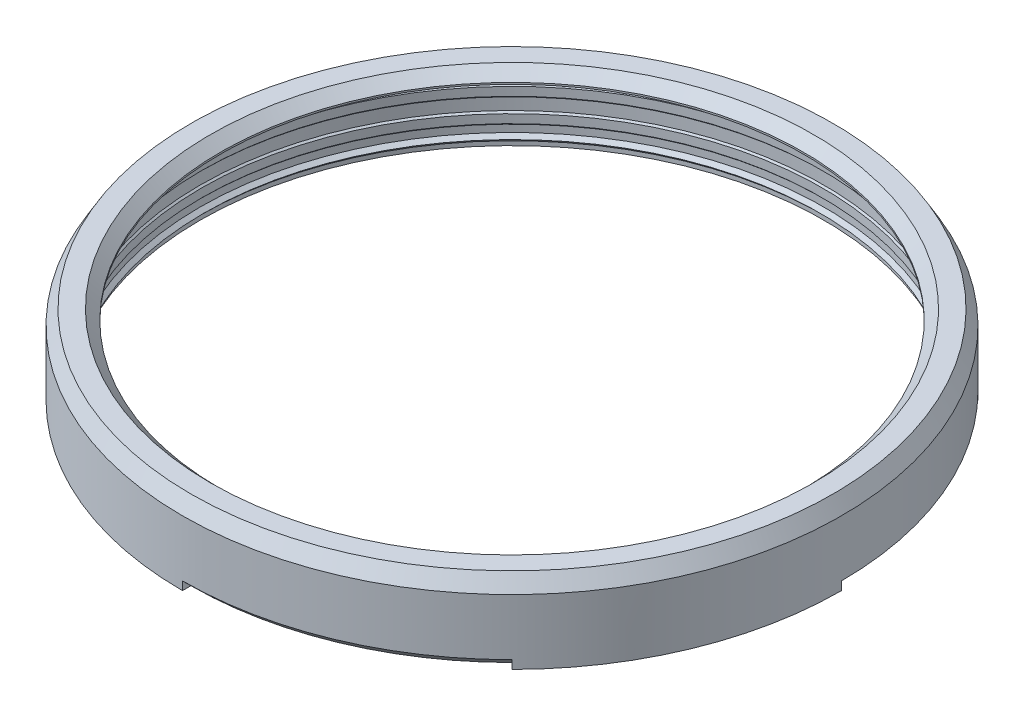
SolidWorks part; units mm, degrees
ref_plane "前视基准面" through (0, 0, 0) normal (0, 0, 1) x (1, 0, 0)
ref_plane "上视基准面" through (0, 0, 0) normal (0, 1, 0) x (1, 0, 0)
ref_plane "右视基准面" through (0, 0, 0) normal (1, 0, 0) x (0, 0, -1)
sketch "草图1" plane through (0, 0, 0) normal (0, 1, 0) x (1, 0, 0)
  circle A0 centre (0, 0) radius 39
  dimension "D1" = 78
extrude "凸台-拉伸1" add sketch "草图1" along normal blind 2
sketch "草图2" plane through (0, 0, 0) normal (-0.866, 0, 0.5) x (0.5, 0, 0.866)
  line L0 (36.93, -8) -> (36.93, -7.5)
  line L1 (36.93, -7.5) -> (36.505, -7.075)
  line L2 (36.505, -7.075) -> (36.93, -6.65)
  line L3 (36.93, -6.65) -> (36.93, -5.8)
  line L4 (36.93, -5.8) -> (36.74, -5.61)
  line L5 (36.74, -5.61) -> (36.74, -4.59)
  line L6 (36.74, -4.59) -> (36.93, -4.4)
  line L7 (36.93, -4.4) -> (36.93, -3)
  line L8 (36.93, -3) -> (36.74, -2.81)
  line L9 (36.74, -2.81) -> (36.74, -1.79)
  line L10 (36.74, -1.79) -> (36.93, -1.6)
  line L11 (36.93, -1.6) -> (36.93, -1.4)
  line L12 (35.53, 0) -> (39, 0)
  line L13 (39, 0) -> (39, -8)
  line L14 (39, -8) -> (36.93, -8)
  line L15 (36.8, -8) -> (38, -8) construction
  line L16 (36.8, -8) -> (36.8, -7.5) construction
  line L17 (0, 0) -> (0, 10.3071) construction
  arc A0 (36.93, -1.4) -> (35.53, 0) centre (35.53, -1.4) ccw
  dimension "D9" = 1.4
  dimension "D1" = 2.26
  dimension "D2" = 8
  dimension "D3" = 0.5
  dimension "D4" = 0.85
  dimension "D5" = 1.4
  dimension "D6" = 1.02
  dimension "D7" = 1.02
  dimension "D8" = 0.2
  dimension "D10" = 135
  dimension "D11" = 0.13
revolve "旋转1" add sketch "草图2" angle 360 about L17
sketch "草图3" plane through (0, 2, 0) normal (0, 1, 0) x (1, 0, 0)
  circle A0 centre (0, 0) radius 34.5
  circle A1 centre (0, 0) radius 39 construction
  dimension "D1" = 4.5
extrude "切除-拉伸1" cut sketch "草图3" against normal through all
sketch "草图4" plane through (0, 2, 0) normal (0, 1, 0) x (1, 0, 0)
  circle A1 centre (0, 0) radius 39
  circle A2 centre (0, 0) radius 39
  dimension "D1" = 0
extrude "切除-拉伸2" cut sketch "草图4" against normal blind 0.6
chamfer "倒角1" distance 1.732 angle 30 1 edges at (0, 1.4, 39)
chamfer "倒角2" distance 1.2 angle 45 1 edges at (0, 1.4, 34.5)
sketch "草图5" plane through (0, 0, 0) normal (0, 0, 1) x (1, 0, 0)
  line L0 (39, -8) -> (39, -7)
  line L1 (39, -8) -> (39, -0.332) construction
  line L2 (39, -7) -> (38, -8)
  line L3 (38.609, -8) -> (37.609, -8) construction
  line L4 (38, -8) -> (39, -8)
  line L6 (0, 0) -> (0, 10.9913) construction
  dimension "D1" = 1
  dimension "D2" = 1
revolve "切除-旋转1" cut sketch "草图5" angle 45 about L6
pattern_circular "阵列(圆周)1" count 4 over 360 about axis through (0, 0, 0) along (0, 1, 0) of "切除-旋转1"
sketch "草图6" plane through (0, 0, 0) normal (0, -1, 0) x (1, 0, 0)
  circle A0 centre (0, 0) radius 35.32
  circle A1 centre (0, 0) radius 35.78
  circle A2 centre (0, 0) radius 34.5 construction
  dimension "D1" = 0.82
  dimension "D2" = 0.46
extrude "凸台-拉伸2" add sketch "草图6" along normal blind 0.5
